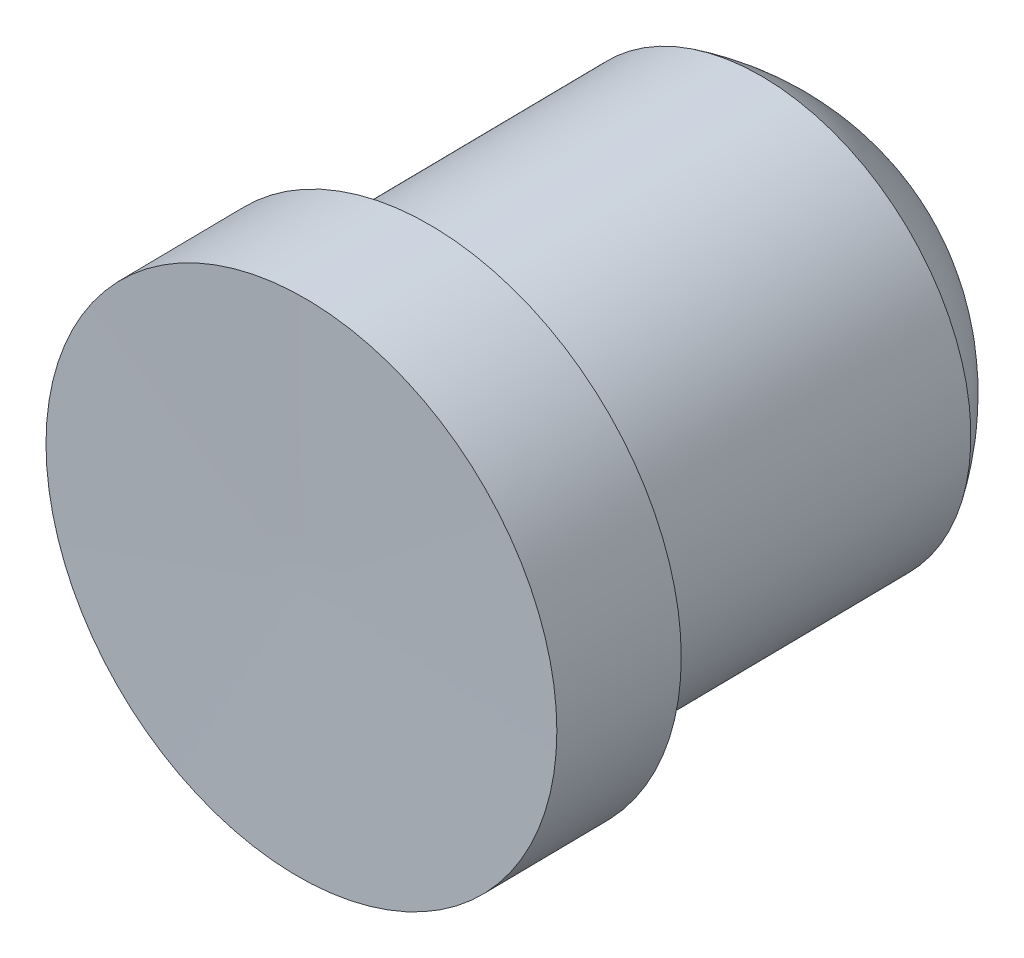
SolidWorks part; units mm, degrees
ref_plane "Front Plane" through (0, 0, 0) normal (0, 0, 1) x (1, 0, 0)
ref_plane "Top Plane" through (0, 0, 0) normal (0, 1, 0) x (1, 0, 0)
ref_plane "Right Plane" through (0, 0, 0) normal (1, 0, 0) x (0, 0, -1)
sketch "Sketch3" plane through (0, 0, 0) normal (0, 1, 0) x (1, 0, 0)
  line L0 (2.6748, 38.6412) -> (2.8814, 23.0318) construction
  line L2 (2.815, 28.0463) -> (5.8153, 28.045)
  line L3 (5.8153, 28.045) -> (5.7954, 29.545)
  line L4 (5.7954, 29.545) -> (5.2954, 29.5452)
  line L5 (5.2954, 29.5452) -> (5.2424, 33.5448)
  line L8 (2.815, 28.0463) -> (2.7233, 34.9758)
  arc A0 (5.2424, 33.5448) -> (2.7233, 34.9758) centre (2.5459, 31.7307) ccw
  dimension "D1" = 5
  dimension "D2" = 4
  dimension "D3" = 6
  dimension "D4" = 1.5
revolve "Revolve1" add sketch "Sketch3" angle 360 about L0
